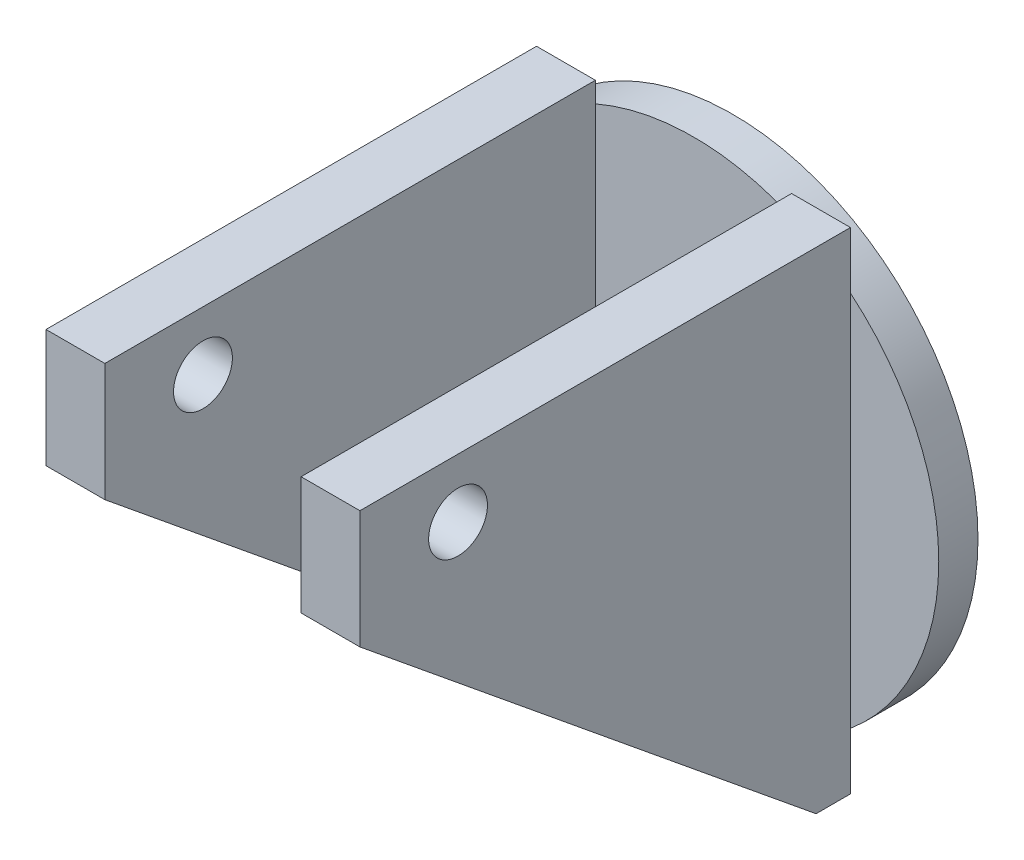
SolidWorks part; units mm, degrees
material "201 Annealed Stainless Steel (SS)"
ref_plane "Front Plane" through (0, 0, 0) normal (0, 0, 1) x (1, 0, 0)
ref_plane "Top Plane" through (0, 0, 0) normal (0, 1, 0) x (1, 0, 0)
ref_plane "Right Plane" through (0, 0, 0) normal (1, 0, 0) x (0, 0, -1)
sketch "Sketch1" plane through (0, 0, 0) normal (0, 0, 1) x (1, 0, 0)
  circle A0 centre (0, 0) radius 12.5
  dimension "D1" = 25
extrude "Boss-Extrude1" add sketch "Sketch1" along normal blind 2
sketch "Sketch2" plane through (0, 0, 0) normal (0, 0, -1) x (-1, 0, 0)
  circle A0 centre (0, 0) radius 2
  dimension "D1" = 4
extrude "Boss-Extrude2" add sketch "Sketch2" along normal blind 1
sketch "Sketch3" plane through (0, 0, 2) normal (0, 0, 1) x (1, 0, 0)
  line L1 (-8, 12.5) -> (-5, 12.5)
  line L2 (-8, 12.5) -> (-8, -12.5)
  line L3 (-8, -12.5) -> (-5, -12.5)
  line L4 (-5, 12.5) -> (-5, -12.5)
  dimension "D1" = 25
  dimension "D2" = 5
  dimension "D3" = 12.5
  dimension "D4" = 3
extrude "Boss-Extrude3" add sketch "Sketch3" along normal blind 25
mirror "Mirror1" about plane through (0, 0, 0) normal (1, 0, 0) of "Boss-Extrude3"
sketch "Sketch5" plane through (-8, 0, 0) normal (-1, 0, 0) x (0, 0, 1)
  line L0 (27, 12.5) -> (2, 12.5) construction
  line L1 (27, 12.5) -> (27, -12.5) construction
  circle A0 centre (22, 9.5) radius 1.5
  dimension "D1" = 3
  dimension "D2" = 3
  dimension "D3" = 5
extrude "Cut-Extrude1" cut sketch "Sketch5" against normal through all
sketch "Sketch6" plane through (8, 0, 0) normal (1, 0, 0) x (0, 0, -1)
  line L0 (-27, 6.4855) -> (-3.7518, -12.5)
  line L1 (-27, 12.5) -> (-27, -12.5) construction
  line L2 (-27, -12.5) -> (-2, -12.5) construction
  line L3 (-3.7518, -12.5) -> (-27, -12.5)
  line L4 (-27, -12.5) -> (-27, 6.4855)
extrude "Cut-Extrude2" cut sketch "Sketch6" against normal through all
